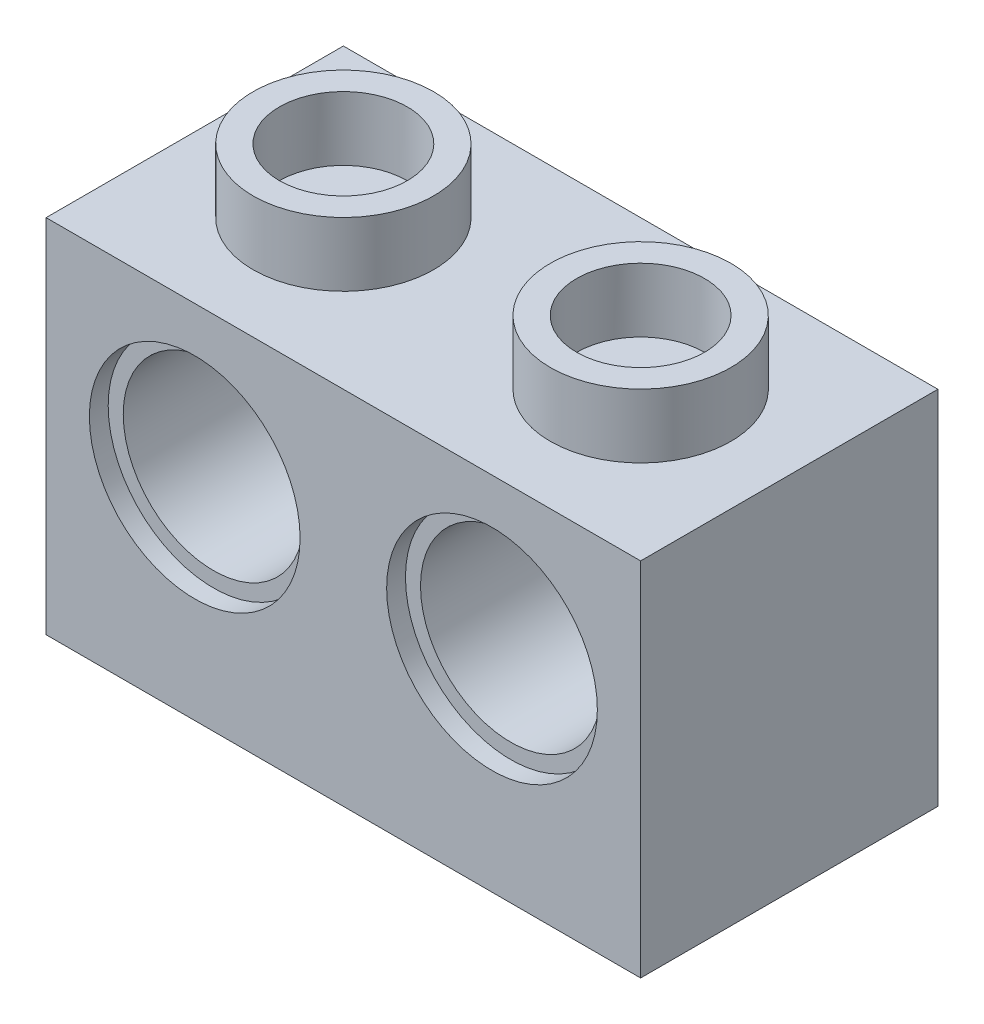
SolidWorks part; units mm, degrees
ref_plane "Front Plane" through (0, 0, 0) normal (0, 0, 1) x (1, 0, 0)
ref_plane "Top Plane" through (0, 0, 0) normal (0, 1, 0) x (1, 0, 0)
ref_plane "Right Plane" through (0, 0, 0) normal (1, 0, 0) x (0, 0, -1)
sketch "Sketch1" plane through (0, 0, 0) normal (0, 1, 0) x (1, 0, 0)
  line L1 (0, 0) -> (7.9, 0)
  line L2 (0, 0) -> (0, 7.9)
  line L3 (0, 7.9) -> (7.9, 7.9)
  line L4 (7.9, 0) -> (7.9, 7.9)
  dimension "D1" = 7.9
  dimension "D2" = 7.9
extrude "Boss-Extrude1" add sketch "Sketch1" along normal blind 9.6
sketch "Sketch2" plane through (0, 0, 0) normal (0, 0, 1) x (1, 0, 0)
  line L0 (3.95, 9.6) -> (3.95, 0) construction
  line L1 (0, 9.6) -> (7.9, 9.6) construction
  line L2 (0, 0) -> (7.9, 0) construction
  line L3 (3.95, 0) -> (3.95, 3.2)
  line L4 (3.95, 9.6) -> (3.95, 7.9983)
  line L5 (3.95, 3.2) -> (3.95, 7.9983)
  circle A0 centre (3.95, 5.5992) radius 2.8
  circle A1 centre (3.95, 5.5992) radius 2.4
  dimension "D2" = 4.8
  dimension "D3" = 5.6
  dimension "D1" = 3.2
extrude "Cut-Extrude1" cut sketch "Sketch2" against normal blind 9.6 contours L4 A1 L3 L5 | L3 A1 L4 L5
sketch "Sketch3" plane through (0, 0, 0) normal (0, 0, 1) x (1, 0, 0)
  line L0 (3.95, 7.9992) -> (3.95, 3.1992)
  circle A0 centre (3.95, 5.5992) radius 2.4 construction
  circle A1 centre (3.95, 5.5992) radius 2.8
  circle M2 centre (3.95, 5.5992) radius 2.4
  dimension "D1" = 5.6
extrude "Cut-Extrude2" cut sketch "Sketch3" against normal blind 0.5 contours A1 L0 M2
sketch "Sketch4" plane through (0, 0, -7.9) normal (0, 0, -1) x (-1, 0, 0)
  line L0 (-3.95, 7.9992) -> (-3.95, 3.1992)
  circle A0 centre (-3.95, 5.5992) radius 2.4 construction
  circle A1 centre (-3.95, 5.5992) radius 2.8
  circle M2 centre (-3.95, 5.5992) radius 2.4
  dimension "D1" = 5.6
extrude "Cut-Extrude3" cut sketch "Sketch4" against normal blind 0.5 contours A1 M2
sketch "Sketch5" plane through (0, 9.6, 0) normal (0, 1, 0) x (1, 0, 0)
  line L0 (0, 7.9) -> (7.9, 0) construction
  circle A0 centre (3.95, 3.95) radius 2.4
  dimension "D1" = 4.8
extrude "Boss-Extrude2" add sketch "Sketch5" along normal blind 1.7
sketch "Sketch6" plane through (0, 11.3, 0) normal (0, 1, 0) x (1, 0, 0)
  line L0 (1.55, 3.95) -> (6.35, 3.95)
  circle A0 centre (3.95, 3.95) radius 2.4 construction
  circle A1 centre (3.95, 3.95) radius 2.4 construction
  circle A2 centre (3.95, 3.95) radius 1.7
  dimension "D1" = 3.4
extrude "Cut-Extrude4" cut sketch "Sketch6" against normal up to surface (1.7 mm away) contours L0 A2 | L0 A2 up to face at (3.95, 9.6, -1.55)
mirror "Mirror1" about plane through (7.9, 9.6, 0) normal (-1, 0, 0) of bodies 106
